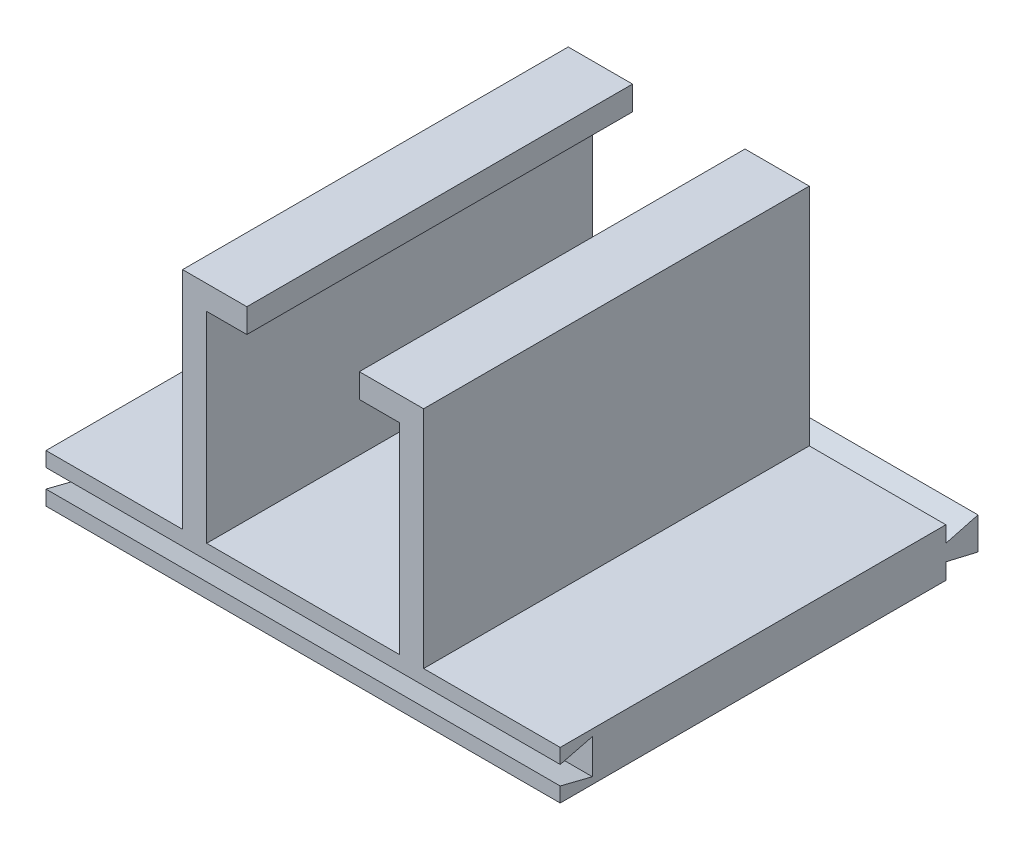
SolidWorks part; units mm, degrees
ref_plane "Front Plane" through (0, 0, 0) normal (0, 0, 1) x (1, 0, 0)
ref_plane "Top Plane" through (0, 0, 0) normal (0, 1, 0) x (1, 0, 0)
ref_plane "Right Plane" through (0, 0, 0) normal (1, 0, 0) x (0, 0, -1)
sketch "Sketch1" plane through (0, 0, 0) normal (0, 1, 0) x (1, 0, 0)
  line L1 (0, 0) -> (101.6, 0)
  line L2 (0, 0) -> (0, 76.2)
  line L3 (0, 76.2) -> (101.6, 76.2)
  line L4 (101.6, 0) -> (101.6, 76.2)
  dimension "D1" = 101.6
  dimension "D2" = 76.2
extrude "Boss-Extrude1" add sketch "Sketch1" along normal blind 9.525
sketch "Sketch2" plane through (0, 9.525, 0) normal (0, 1, 0) x (1, 0, 0)
  line L0 (0, 0) -> (101.6, 0) construction
  line L5 (26.9875, 0) -> (31.75, 0)
  line L6 (26.9875, 0) -> (26.9875, 76.2)
  line L7 (26.9875, 76.2) -> (31.75, 76.2)
  line L8 (31.75, 0) -> (31.75, 76.2)
  line L9 (101.6, 76.2) -> (0, 76.2) construction
  point P8 (50.8, 0)
  dimension "D1" = 19.05
  dimension "D2" = 4.7625
extrude "Boss-Extrude2" add sketch "Sketch2" along normal blind 44.45
sketch "Sketch3" plane through (31.75, 0, 0) normal (1, 0, 0) x (0, 0, -1)
  line L0 (76.2, 53.975) -> (76.2, 9.525) construction
  line L1 (0, 53.975) -> (76.2, 53.975)
  line L2 (0, 53.975) -> (0, 49.2125)
  line L3 (0, 49.2125) -> (76.2, 49.2125)
  line L4 (76.2, 53.975) -> (76.2, 49.2125)
  dimension "D1" = 4.7625
extrude "Boss-Extrude3" add sketch "Sketch3" along normal blind 7.9375
ref_plane "Plane1" through (50.8, 0, 0) normal (1, 0, 0) x (0, 0, -1)
mirror "Mirror1" about plane through (50.8, 0, 0) normal (1, 0, 0) of "Boss-Extrude3", "Boss-Extrude2"
sketch "Sketch7" plane through (101.6, 0, 0) normal (1, 0, 0) x (0, 0, -1)
  line L5 (76.2, 3.175) -> (76.2, 6.35)
  line L6 (76.2, 9.525) -> (76.2, 0) construction
  line L7 (76.2, 6.35) -> (82.55, 8.0329)
  line L8 (82.55, 8.0329) -> (82.55, 1.6822)
  line L9 (82.55, 1.6822) -> (76.2, 3.175)
  line L10 (76.2, 4.7625) -> (82.55, 4.8576) construction
  point P9 (82.55, 4.8576)
  dimension "D1" = 3.175
  dimension "D2" = 3.175
  dimension "D3" = 3.175
  dimension "D4" = 3.175
  dimension "D5" = 6.35
  dimension "D6" = 6.3507
extrude "Boss-Extrude4" add sketch "Sketch7" against normal blind 101.6
sketch "Sketch9" plane through (101.6, 0, 0) normal (1, 0, 0) x (0, 0, -1)
  line L0 (0, 2.921) -> (0, 6.604)
  line L1 (0, 9.525) -> (0, 0) construction
  line L2 (0, 6.604) -> (6.35, 8.1915)
  line L3 (6.35, 8.1915) -> (6.35, 1.3335)
  line L4 (6.35, 1.3335) -> (0, 2.921)
  line L5 (0, 4.7625) -> (7.9996, 4.7625) construction
  point P10 (6.35, 4.7625)
  dimension "D1" = 2.921
  dimension "D2" = 3.683
  dimension "D3" = 3.429
  dimension "D4" = 3.429
  dimension "D5" = 6.35
extrude "Cut-Extrude1" cut sketch "Sketch9" against normal through all
